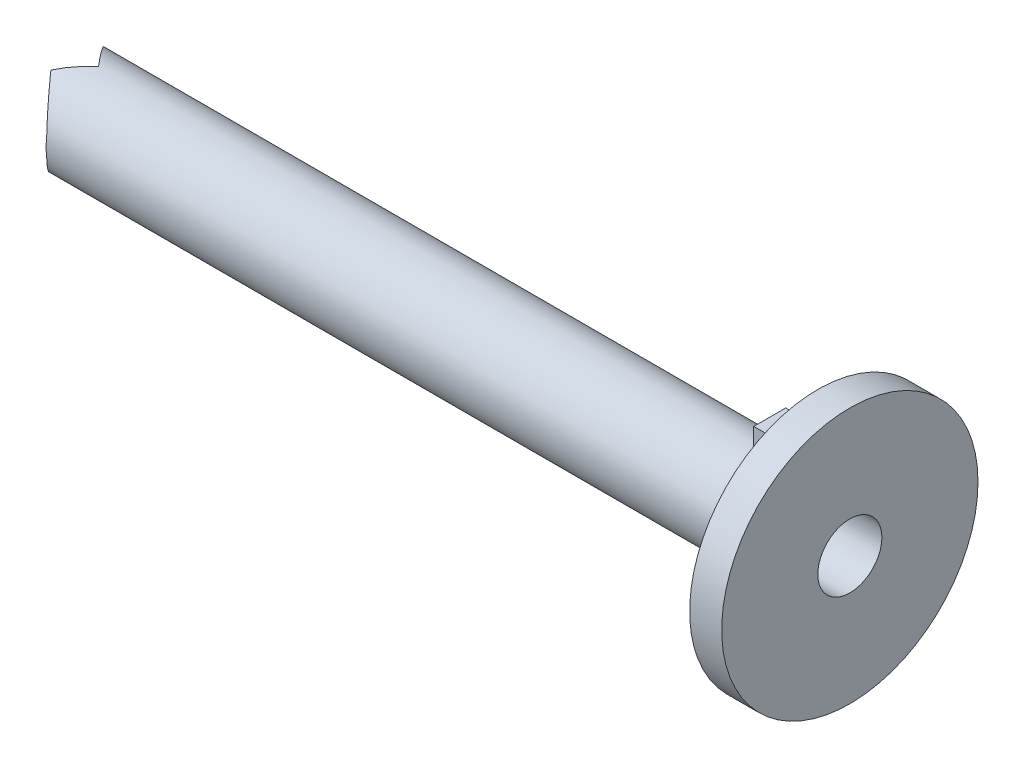
SolidWorks part; units mm, degrees
material "ABS PC"
ref_plane "Front Plane" through (0, 0, 0) normal (0, 0, 1) x (1, 0, 0)
ref_plane "Top Plane" through (0, 0, 0) normal (0, 1, 0) x (1, 0, 0)
ref_plane "Right Plane" through (0, 0, 0) normal (1, 0, 0) x (0, 0, -1)
sketch "Sketch1" plane through (0, 0, 0) normal (1, 0, 0) x (0, 0, -1)
  circle A0 centre (0, 0) radius 12.7
  circle A1 centre (0, 0) radius 19.05
  dimension "D1" = 25.4
  dimension "D2" = 38.1
extrude "Boss-Extrude1" add sketch "Sketch1" against normal blind 381
sketch "Sketch2" plane through (0, 0, 0) normal (1, 0, 0) x (0, 0, -1)
  circle A0 centre (0, 0) radius 50.8
  circle A1 centre (0, 0) radius 12.7 construction
  circle A2 centre (0, 0) radius 12.7
  dimension "D1" = 101.6
extrude "Boss-Extrude2" add sketch "Sketch2" against normal blind 12.7
sketch "Sketch3" plane through (0, 0, 0) normal (0, 1, 0) x (1, 0, 0)
  line L0 (-330.0495, 38.4656) -> (-297.8458, 0)
  line L1 (-297.8458, 0) -> (-308.1196, -8.6013)
  line L2 (-308.1196, -8.6013) -> (-299.508, -18.8873)
  line L3 (-299.508, -18.8873) -> (-330.0495, -60.5311)
  line L4 (-330.0495, -60.5311) -> (-403.4025, -60.5311)
  line L5 (-403.4025, -60.5311) -> (-403.4025, 38.4656)
  line L6 (-403.4025, 38.4656) -> (-330.0495, 38.4656)
extrude "Cut-Extrude1" cut sketch "Sketch3" against normal through all and the other way through all
sketch "Sketch4" plane through (0, 0, 0) normal (0, 1, 0) x (1, 0, 0)
  line L0 (0, -50.8) -> (0, 50.8) construction
  line L1 (-31.75, -6.35) -> (-19.05, -6.35)
  line L2 (-31.75, -6.35) -> (-31.75, 6.35)
  line L3 (-31.75, 6.35) -> (-19.05, 6.35)
  line L4 (-19.05, -6.35) -> (-19.05, 6.35)
  line L5 (-31.75, -6.35) -> (-19.05, 6.35) construction
  line L6 (-31.75, 6.35) -> (-19.05, -6.35) construction
  circle A0 centre (-25.4, 0) radius 2.286
  point P0 (-25.4, 0)
  dimension "D3" = 4.572
  dimension "D1" = 25.4
  dimension "D2" = 12.7
extrude "Boss-Extrude3" add sketch "Sketch4" against normal up to next from offset 31.75
